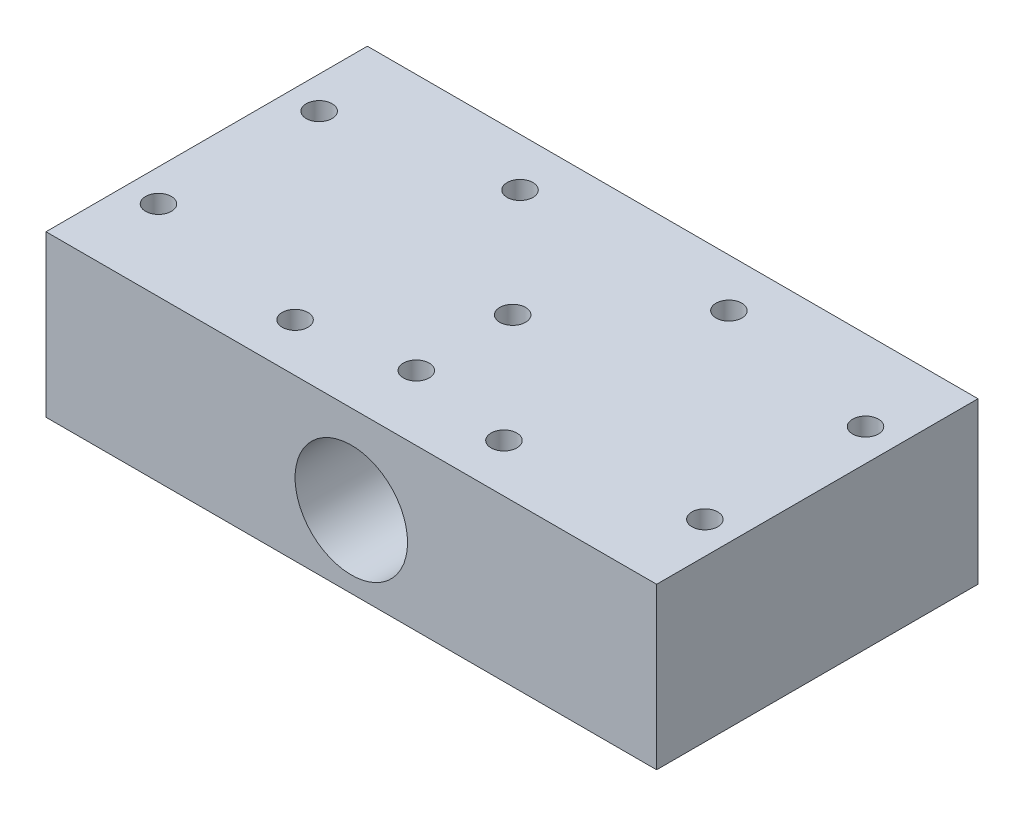
SolidWorks part; units mm, degrees
ref_plane "Front Plane" through (0, 0, 0) normal (0, 0, 1) x (1, 0, 0)
ref_plane "Top Plane" through (0, 0, 0) normal (0, 1, 0) x (1, 0, 0)
ref_plane "Right Plane" through (0, 0, 0) normal (1, 0, 0) x (0, 0, -1)
sketch "Sketch1" plane through (0, 0, 0) normal (1, 0, 0) x (0, 0, -1)
  line L1 (-31.75, 15.875) -> (31.75, 15.875)
  line L2 (-31.75, 15.875) -> (-31.75, -15.875)
  line L3 (-31.75, -15.875) -> (31.75, -15.875)
  line L4 (31.75, 15.875) -> (31.75, -15.875)
  line L5 (-31.75, 15.875) -> (31.75, -15.875) construction
  line L6 (-31.75, -15.875) -> (31.75, 15.875) construction
  point P0 (0, 0)
  dimension "D1" = 63.5
  dimension "D2" = 31.75
extrude "Boss-Extrude1" add sketch "Sketch1" against normal blind 120.65
sketch "Sketch5" plane through (0, 0, -31.75) normal (0, 0, -1) x (-1, 0, 0)
  line L4 (0, 15.875) -> (0, -15.875)
  line L5 (0, -15.875) -> (120.65, -15.875)
  line L6 (120.65, -15.875) -> (120.65, 15.875)
  line L7 (120.65, 15.875) -> (0, 15.875)
  line L8 (0, 15.875) -> (0, -15.875)
  line L9 (0, -15.875) -> (120.65, -15.875)
  line L10 (120.65, -15.875) -> (120.65, 15.875)
  line L11 (120.65, 15.875) -> (0, 15.875)
  dimension "D1" = 0
extrude "Cut-Extrude1" [suppressed] cut sketch "Sketch5" against normal blind 3.3528
hole_wizard "Hole1" positions "Sketch4" profile "Sketch3" legacy end condition up to next
sketch "Sketch4" plane through (0, 0, 31.75) normal (0, 0, 1) x (1, 0, 0)
  line L0 (0, -1.5875) -> (-120.65, -1.5875) construction
  line L1 (0, 15.875) -> (0, -15.875) construction
  line L2 (-120.65, 15.875) -> (-120.65, -15.875) construction
  line L4 (-120.65, -15.875) -> (0, -15.875) construction
  point P22 (-60.325, -1.5875)
  dimension "D1" = 60.325
  dimension "D4" = 14.2875
sketch "Sketch3" plane through (-60.325, -1.5875, 31.75) normal (1, 0, 0) x (0, -1, 0)
  line L0 (0, 0) -> (0, 63.5)
  line L1 (0, 63.5) -> (11.1125, 63.5)
  line L2 (11.1125, 63.5) -> (11.1125, 0)
  line L3 (11.1125, 0) -> (0, 0)
  line L4 (0, 110) -> (0, -10) construction
  dimension "Diameter" = 22.225
  dimension "Depth" = 63.5
hole_wizard "Tapped Hole for #10-32 Helicoil1" [suppressed] positions "Sketch7" profile "Sketch8" tap size "#10-32" standard "Helicoil® Inch"
sketch "Sketch7" plane through (0, 15.875, 0) normal (0, 1, 0) x (1, 0, 0)
  line L0 (-63.5, 11.0236) -> (-63.5, -11.0236) construction
  line L1 (-127, 11.0236) -> (0, 11.0236) construction
  line L2 (-127, -11.0236) -> (0, -11.0236) construction
  line L3 (0, 11.0236) -> (0, -11.0236) construction
  point P8 (-63.5, -6.2611)
  point P10 (-63.5, 6.2611)
  dimension "D1" = 63.5
  dimension "D2" = 4.7625
  dimension "D3" = 4.7625
sketch "Sketch8" plane through (-63.5, 15.875, 6.2611) normal (1, 0, 0) x (0, 0, 1)
  line L0 (0, 0) -> (0, 13.4718)
  line L1 (0, 13.4718) -> (2.5527, 11.938)
  line L2 (2.5527, 11.938) -> (2.5527, 0)
  line L5 (2.5527, 0) -> (0, 0)
  line L10 (0, 13.4718) -> (-2.5527, 11.938) construction
  line L11 (0, -6.35) -> (0, 107.95) construction
  dimension "Tap Drill Dia." = 5.1054
  dimension "Tap Drill Depth" = 11.938
  dimension "Drill Angle" = 118
cosmetic thread "Hole Thread1" [suppressed] parameters "D1"=5.0597, "D2"=5.936
cosmetic thread "Hole Thread2" [suppressed] parameters "D1"=5.0597, "D2"=5.936
sketch "Sketch9" plane through (0, 0, 31.75) normal (0, 0, 1) x (1, 0, 0)
  line L0 (-120.65, -15.875) -> (0, -15.875) construction
  line L1 (-79.375, -15.875) -> (-34.925, -15.875)
  line L2 (-79.375, -15.875) -> (-79.375, 6.35)
  line L3 (-79.375, 6.35) -> (-34.925, 6.35)
  line L4 (-34.925, -15.875) -> (-34.925, 6.35)
  line L5 (-79.375, 6.35) -> (-34.925, -15.875) construction
  line L6 (-57.15, -4.7625) -> (-57.15, 15.875) construction
  line L7 (-120.65, 15.875) -> (0, 15.875) construction
  line L8 (0, 15.875) -> (0, -15.875) construction
  dimension "D1" = 9.525
  dimension "D2" = 57.15
  dimension "D3" = 44.45
extrude "Cut-Extrude2" [suppressed] cut sketch "Sketch9" against normal up to next
sketch "Sketch12" plane through (0, 15.875, 0) normal (0, 1, 0) x (1, 0, 0)
  line L0 (-73.025, 0) -> (-41.275, 0) construction
  line L1 (0, 31.75) -> (0, -31.75) construction
  line L2 (-74.6125, 0) -> (-71.4375, 0) construction
  line L3 (-74.6125, 3.175) -> (-71.4375, 3.175)
  line L4 (-74.6125, -3.175) -> (-71.4375, -3.175)
  line L5 (-42.8625, 0) -> (-39.6875, 0) construction
  line L6 (-42.8625, 3.175) -> (-39.6875, 3.175)
  line L7 (-42.8625, -3.175) -> (-39.6875, -3.175)
  arc A0 (-74.6125, 3.175) -> (-74.6125, -3.175) centre (-74.6125, 0) ccw
  arc A1 (-71.4375, -3.175) -> (-71.4375, 3.175) centre (-71.4375, 0) ccw
  arc A2 (-42.8625, 3.175) -> (-42.8625, -3.175) centre (-42.8625, 0) ccw
  arc A3 (-39.6875, -3.175) -> (-39.6875, 3.175) centre (-39.6875, 0) ccw
  point P7 (-73.025, 0)
  point P13 (-41.275, 0)
  dimension "D4" = 3.175
  dimension "D1" = 41.275
  dimension "D2" = 31.75
  dimension "D3" = 3.175
extrude "Cut-Extrude3" [suppressed] cut sketch "Sketch12" against normal up to next
sketch "Sketch13" plane through (0, 15.875, 0) normal (0, 1, 0) x (1, 0, 0)
  line L0 (-73.025, 0) -> (-41.275, 0) construction
  line L1 (0, 31.75) -> (0, -31.75) construction
  line L2 (-74.6125, 0) -> (-71.4375, 0) construction
  line L3 (-74.6125, 6.35) -> (-71.4375, 6.35)
  line L4 (-74.6125, -6.35) -> (-71.4375, -6.35)
  line L5 (-42.8625, 0) -> (-39.6875, 0) construction
  line L6 (-42.8625, 6.35) -> (-39.6875, 6.35)
  line L7 (-42.8625, -6.35) -> (-39.6875, -6.35)
  arc A0 (-74.6125, 6.35) -> (-74.6125, -6.35) centre (-74.6125, 0) ccw
  arc A1 (-71.4375, -6.35) -> (-71.4375, 6.35) centre (-71.4375, 0) ccw
  arc A2 (-42.8625, 6.35) -> (-42.8625, -6.35) centre (-42.8625, 0) ccw
  arc A3 (-39.6875, -6.35) -> (-39.6875, 6.35) centre (-39.6875, 0) ccw
  point P7 (-73.025, 0)
  point P13 (-41.275, 0)
  dimension "D3" = 6.35
  dimension "D1" = 31.75
  dimension "D2" = 41.275
  dimension "D4" = 3.175
extrude "Cut-Extrude4" [suppressed] cut sketch "Sketch13" against normal blind 6.35
sketch "Sketch14" plane through (0, 0, -31.75) normal (0, 0, -1) x (-1, 0, 0)
  line L0 (0, -15.875) -> (0, 15.875) construction
  line L1 (0, 13.335) -> (30.1625, 13.335)
  line L2 (0, 13.335) -> (0, -15.875)
  line L3 (0, -15.875) -> (36.5125, -15.875)
  line L4 (36.5125, 6.985) -> (36.5125, -15.875)
  line L6 (120.65, -15.875) -> (0, -15.875) construction
  line L7 (120.65, 15.875) -> (0, 15.875) construction
  line L9 (101.6, 13.335) -> (77.7875, 13.335)
  line L10 (107.95, 6.985) -> (107.95, -15.875)
  line L11 (107.95, -15.875) -> (71.4375, -15.875)
  line L12 (71.4375, 6.985) -> (71.4375, -15.875)
  line L13 (120.65, -15.875) -> (120.65, 15.875) construction
  line L14 (120.65, -15.875) -> (0, -15.875) construction
  arc A0 (77.7875, 13.335) -> (71.4375, 6.985) centre (77.7875, 6.985) ccw
  arc A1 (30.1625, 13.335) -> (36.5125, 6.985) centre (30.1625, 6.985) cw
  arc A2 (101.6, 13.335) -> (107.95, 6.985) centre (101.6, 6.985) cw
  dimension "D2" = 6.35
  dimension "D4" = 6.35
  dimension "D1" = 2.54
  dimension "D3" = 12.7
  dimension "D5" = 36.5125
extrude "Cut-Extrude5" [suppressed] cut sketch "Sketch14" against normal blind 5.08
mirror "Mirror1" [suppressed] about plane through (0, 0, 0) normal (0, 0, 1)
hole_wizard "Tapped Hole for #10-32 Helicoil2" [suppressed] positions "Sketch16" profile "Sketch17" tap size "#10-32" standard "Helicoil® Inch"
sketch "Sketch16" plane through (0, 19.05, 0) normal (0, 1, 0) x (1, 0, 0)
  line L0 (0, 0) -> (-127, 0) construction
  line L1 (-127, 15.875) -> (-127, -15.875) construction
  line L2 (0, 15.875) -> (0, -15.875) construction
  point P7 (-109.5375, 0)
  point P9 (-4.7625, 0)
  dimension "D1" = 4.7625
  dimension "D2" = 104.775
sketch "Sketch17" plane through (-109.5375, 19.05, 0) normal (1, 0, 0) x (0, 0, 1)
  line L0 (0, 0) -> (0, 18.5518)
  line L1 (0, 18.5518) -> (2.5527, 17.018)
  line L2 (2.5527, 17.018) -> (2.5527, 0)
  line L5 (2.5527, 0) -> (0, 0)
  line L10 (0, 18.5518) -> (-2.5527, 17.018) construction
  line L11 (0, -6.35) -> (0, 107.95) construction
  dimension "Tap Drill Dia." = 5.1054
  dimension "Tap Drill Depth" = 17.018
  dimension "Drill Angle" = 118
cosmetic thread "Hole Thread3" [suppressed] parameters "D1"=11.43, "D2"=5.936
cosmetic thread "Hole Thread4" [suppressed] parameters "D1"=11.43, "D2"=5.936
hole_wizard "#4-40 Tapped Hole1" [suppressed] positions "Sketch19" profile "Sketch18" tap size "#4-40" standard "ANSI Inch"
sketch "Sketch19" plane through (-127, 0, 0) normal (-1, 0, 0) x (0, 0, 1)
  line L0 (-10.4775, 6.35) -> (10.4775, 6.35) construction
  line L2 (0, 6.35) -> (0, 19.05) construction
  line L3 (-15.875, 19.05) -> (15.875, 19.05) construction
  point P0 (-10.4775, 6.35)
  point P1 (10.4775, 6.35)
  dimension "D1" = 20.955
  dimension "D2" = 12.7
sketch "Sketch18" plane through (-127, 6.35, -10.4775) normal (0, 1, 0) x (0, 0, 1)
  line L0 (0, 0) -> (0, 13.3792)
  line L1 (0, 13.3792) -> (1.1303, 12.7)
  line L2 (1.1303, 12.7) -> (1.1303, 0)
  line L5 (1.1303, 0) -> (0, 0)
  line L10 (0, 13.3792) -> (-1.1303, 12.7) construction
  line L11 (0, -6.35) -> (0, 107.95) construction
  dimension "Tap Drill Dia." = 2.2606
  dimension "Tap Drill Depth" = 12.7
  dimension "Drill Angle" = 118
cosmetic thread "Hole Thread5" [suppressed] parameters "D1"=5.588, "D2"=2.8448
cosmetic thread "Hole Thread6" [suppressed] parameters "D1"=5.588, "D2"=2.8448
hole_wizard "Tapped Hole for #10-32 Helicoil3" positions "Sketch22" profile "Sketch21" tap size "#10-32" standard "Helicoil® Inch"
sketch "Sketch22" plane through (-13.6624, 15.875, 9.154) normal (0, 1, 0) x (1, 0, 0)
  line L0 (-46.6626, 40.904) -> (-46.6626, -22.596) construction
  line L1 (-106.9876, 40.904) -> (13.6624, 40.904) construction
  line L2 (-106.9876, -22.596) -> (13.6624, -22.596) construction
  point P8 (-46.6626, 9.2891)
  point P10 (-46.6626, -9.7609)
  dimension "D1" = 19.05
cosmetic thread "Hole Thread7" parameters "D1"=3.4722, "D2"=5.936
cosmetic thread "Hole Thread8" parameters "D1"=3.4722, "D2"=5.936
sketch "Sketch21" plane through (-60.325, 15.875, -0.1352) normal (1, 0, 0) x (0, 0, 1)
  line L0 (0, 0) -> (0, 6.35)
  line L1 (0, 6.35) -> (2.5527, 6.35)
  line L2 (2.5527, 6.35) -> (2.5527, 0)
  line L5 (2.5527, 0) -> (0, 0)
  line L11 (0, -6.35) -> (0, 107.95) construction
  dimension "Thru Tap Drill Dia." = 5.1054
  dimension "Thru Tap Drill Depth" = 6.35
hole_wizard "Tapped Hole for #10-32 Helicoil4" positions "Sketch24" profile "Sketch23" tap size "#10-32" standard "Helicoil® Inch" end condition through all
sketch "Sketch24" plane through (0, 15.875, 0) normal (0, 1, 0) x (1, 0, 0)
  line L0 (-114.3, 31.75) -> (-114.3, -31.75) construction
  line L1 (-120.65, 31.75) -> (0, 31.75) construction
  line L2 (-120.65, -31.75) -> (0, -31.75) construction
  line L4 (-6.35, 31.75) -> (-6.35, -31.75) construction
  line L5 (-120.65, 31.75) -> (-120.65, -31.75) construction
  line L6 (0, 31.75) -> (0, -31.75) construction
  point P12 (-114.3, 15.875)
  point P14 (-114.3, -15.875)
  point P16 (-6.35, -15.875)
  point P18 (-6.35, 15.875)
  dimension "D1" = 6.35
  dimension "D2" = 6.35
  dimension "D3" = 15.875
  dimension "D4" = 15.875
sketch "Sketch23" plane through (-114.3, 15.875, -15.875) normal (1, 0, 0) x (0, 0, 1)
  line L0 (0, 0) -> (0, 31.75)
  line L1 (0, 31.75) -> (2.5527, 31.75)
  line L2 (2.5527, 31.75) -> (2.5527, 0)
  line L5 (2.5527, 0) -> (0, 0)
  line L11 (0, -6.35) -> (0, 107.95) construction
  dimension "Thru Tap Drill Dia." = 5.1054
  dimension "Thru Tap Drill Depth" = 31.75
cosmetic thread "Hole Thread17" parameters "D1"=15.875, "D2"=5.936
cosmetic thread "Hole Thread18" parameters "D1"=15.875, "D2"=5.936
cosmetic thread "Hole Thread19" parameters "D1"=15.875, "D2"=5.936
cosmetic thread "Hole Thread20" parameters "D1"=15.875, "D2"=5.936
hole_wizard "Tapped Hole for #10-32 Helicoil5" positions "Sketch26" profile "Sketch25" tap size "#10-32" standard "Helicoil® Inch"
sketch "Sketch26" plane through (0, 15.875, 0) normal (0, 1, 0) x (1, 0, 0)
  line L1 (-80.9625, 22.225) -> (-39.6875, 22.225) construction
  line L2 (-80.9625, 22.225) -> (-80.9625, -22.225) construction
  line L3 (-80.9625, -22.225) -> (-39.6875, -22.225) construction
  line L4 (-39.6875, 22.225) -> (-39.6875, -22.225) construction
  line L5 (-39.6875, 0) -> (0, 0) construction
  point P0 (-80.9625, 22.225)
  point P1 (-39.6875, -22.225)
  point P136 (-80.9625, -22.225)
  point P137 (-39.6875, 22.225)
  dimension "D1" = 41.275
  dimension "D2" = 44.45
  dimension "D3" = 39.6875
sketch "Sketch25" plane through (-80.9625, 15.875, -22.225) normal (1, 0, 0) x (0, 0, 1)
  line L0 (0, 0) -> (0, 18.5518)
  line L1 (0, 18.5518) -> (2.5527, 17.018)
  line L2 (2.5527, 17.018) -> (2.5527, 0)
  line L5 (2.5527, 0) -> (0, 0)
  line L10 (0, 18.5518) -> (-2.5527, 17.018) construction
  line L11 (0, -6.35) -> (0, 107.95) construction
  dimension "Tap Drill Dia." = 5.1054
  dimension "Tap Drill Depth" = 17.018
  dimension "Drill Angle" = 118
cosmetic thread "Hole Thread13" parameters "D1"=11.43, "D2"=5.936
cosmetic thread "Hole Thread14" parameters "D1"=11.43, "D2"=5.936
cosmetic thread "Hole Thread15" parameters "D1"=11.43, "D2"=5.936
cosmetic thread "Hole Thread16" parameters "D1"=11.43, "D2"=5.936
sketch "Sketch29" plane through (0, 15.875, 0) normal (0, 1, 0) x (1, 0, 0)
  line L0 (-120.65, 22.225) -> (-120.65, 9.525)
  line L1 (-120.65, 31.75) -> (-120.65, -31.75) construction
  line L2 (-120.65, 9.525) -> (-114.3, 9.525)
  line L3 (-114.3, 22.225) -> (-120.65, 22.225)
  line L4 (-114.3, -9.525) -> (-120.65, -9.525)
  line L5 (-120.65, -9.525) -> (-120.65, -22.225)
  line L6 (-120.65, -22.225) -> (-114.3, -22.225)
  line L7 (-60.325, 31.75) -> (-60.325, -31.75) construction
  line L8 (-120.65, 31.75) -> (0, 31.75) construction
  line L9 (-120.65, -31.75) -> (0, -31.75) construction
  line L10 (0, -22.225) -> (-6.35, -22.225)
  line L11 (0, -9.525) -> (0, -22.225)
  line L12 (-6.35, -9.525) -> (0, -9.525)
  line L13 (-6.35, 22.225) -> (0, 22.225)
  line L14 (0, 9.525) -> (-6.35, 9.525)
  line L15 (0, 22.225) -> (0, 9.525)
  arc A0 (-114.3, 9.525) -> (-114.3, 22.225) centre (-114.3, 15.875) ccw
  arc A1 (-114.3, -22.225) -> (-114.3, -9.525) centre (-114.3, -15.875) ccw
  circle A2 centre (-114.3, -15.875) radius 2.5527 construction
  circle A3 centre (-114.3, 15.875) radius 2.5527 construction
  arc A4 (-6.35, -22.225) -> (-6.35, -9.525) centre (-6.35, -15.875) cw
  arc A5 (-6.35, 9.525) -> (-6.35, 22.225) centre (-6.35, 15.875) cw
  dimension "D1" = 6.35
extrude "Cut-Extrude7" [suppressed] cut sketch "Sketch29" against normal blind 6.35
